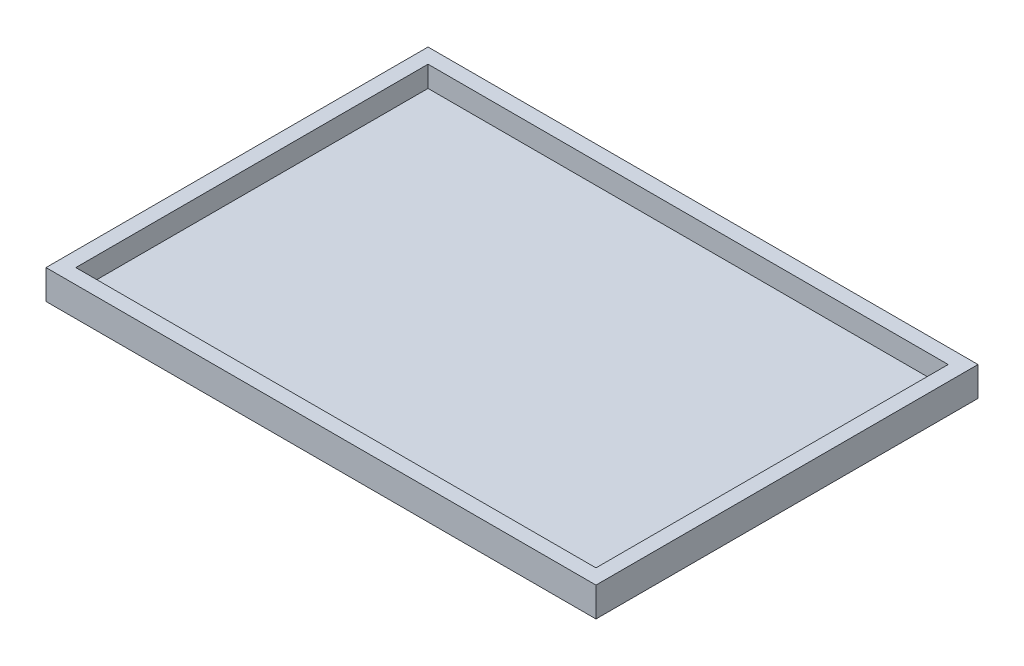
SolidWorks part; units mm, degrees
ref_plane "Front Plane" through (0, 0, 0) normal (0, 0, 1) x (1, 0, 0)
ref_plane "Top Plane" through (0, 0, 0) normal (0, 1, 0) x (1, 0, 0)
ref_plane "Right Plane" through (0, 0, 0) normal (1, 0, 0) x (0, 0, -1)
sketch "Sketch1" plane through (0, 0, 0) normal (0, 1, 0) x (1, 0, 0)
  line L1 (-65.5, -45.5) -> (65.5, -45.5)
  line L2 (-65.5, -45.5) -> (-65.5, 45.5)
  line L3 (-65.5, 45.5) -> (65.5, 45.5)
  line L4 (65.5, -45.5) -> (65.5, 45.5)
  line L5 (-65.5, -45.5) -> (65.5, 45.5) construction
  line L6 (-65.5, 45.5) -> (65.5, -45.5) construction
  point P0 (0, 0)
  dimension "D1" = 91
  dimension "D2" = 131
extrude "Boss-Extrude1" add sketch "Sketch1" along normal blind 7
sketch "Sketch2" plane through (0, 7, 0) normal (0, 1, 0) x (1, 0, 0)
  line L1 (-61.95, -41.95) -> (61.95, -41.95)
  line L2 (-61.95, -41.95) -> (-61.95, 41.95)
  line L3 (-61.95, 41.95) -> (61.95, 41.95)
  line L4 (61.95, -41.95) -> (61.95, 41.95)
  line L5 (-61.95, -41.95) -> (61.95, 41.95) construction
  line L6 (-61.95, 41.95) -> (61.95, -41.95) construction
  point P0 (0, 0)
  dimension "D1" = 83.9
  dimension "D2" = 123.9
extrude "Cut-Extrude1" cut sketch "Sketch2" against normal blind 5
